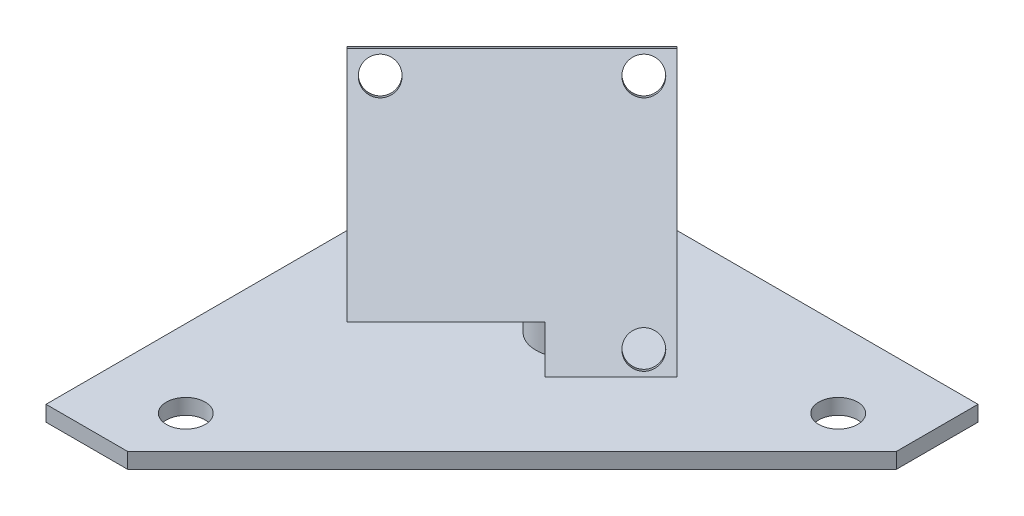
SolidWorks part; units mm, degrees
ref_plane "Front" through (0, 0, 0) normal (0, 0, 1) x (1, 0, 0)
ref_plane "Top" through (0, 0, 0) normal (0, 1, 0) x (1, 0, 0)
ref_plane "Right" through (0, 0, 0) normal (1, 0, 0) x (0, 0, -1)
sketch "草图1" plane through (0, 0, 0) normal (0, 1, 0) x (1, 0, 0)
  line L0 (87.1745, 16.672) -> (1.4976, -69.0049)
  line L1 (0, 0) -> (60, 0)
  line L2 (0, 0) -> (0, -60)
  line L3 (0, -60) -> (60, -60)
  line L4 (60, 0) -> (60, -60)
  line L5 (0, 0) -> (20, 0)
  line L6 (0, 0) -> (0, -20)
  line L7 (0, -20) -> (20, -20)
  line L8 (20, 0) -> (20, -20)
  circle A0 centre (10, -52) radius 2.5
  circle A1 centre (52, -10) radius 2.5
  dimension "D5" = 5
  dimension "D8" = 5
  dimension "D1" = 60
  dimension "D2" = 60
  dimension "D3" = 20
  dimension "D4" = 20
  dimension "D6" = 10
  dimension "D7" = 8
  dimension "D9" = 10
  dimension "D10" = 8
  dimension "D11" = 35
extrude "凸台-拉伸1" add sketch "草图1" along normal blind 2 contours L1 L8 L7 L2 L3 L4
ref_plane "基准面1" through (23.1124, 18.8712, 23.1124) normal (0.6124, 0.5, 0.6124) x (-0.7071, 0, 0.7071)
sketch "草图2" plane through (23.1124, 18.8712, 23.1124) normal (0.6124, 0.5, 0.6124) x (-0.7071, 0, 0.7071)
  line L0 (20.7547, -10.714) -> (-21.3736, -10.714) construction
  line L1 (-15, 16.786) -> (15, 16.786)
  line L2 (-15, 16.786) -> (-15, -13.214)
  line L3 (-15, -13.214) -> (15, -13.214)
  line L4 (15, 16.786) -> (15, -13.214)
  line L5 (-15, 16.786) -> (15, -13.214) construction
  line L6 (-15, -13.214) -> (15, 16.786) construction
  line L7 (0, -2.8326) -> (0, 36.0846) construction
  line L8 (27.4605, 1.786) -> (-33.4746, 1.786) construction
  line L10 (15, 16.786) -> (-3, 16.786)
  line L11 (15, 16.786) -> (15, 11.786)
  line L12 (15, 11.786) -> (-3, 11.786)
  line L13 (-3, 16.786) -> (-3, 11.786)
  circle A0 centre (12, -10.714) radius 2
  circle A1 centre (-12, -10.714) radius 2
  circle A2 centre (-12, 14.286) radius 2
  circle A3 centre (12, 14.286) radius 2
  point P0 (0, 1.786)
  point P23 (0, 1.786)
  dimension "D4" = 4
  dimension "D1" = 30
  dimension "D2" = 30
  dimension "D3" = 12.5
  dimension "D5" = 12
  dimension "D6" = 5
  dimension "D7" = 18
extrude "凸台-拉伸3" add sketch "草图2" along normal blind 2 separate body contours L13 L1 L2 L3 L4 L12 A2 A0 A1
sketch "草图4" plane through (0, 2, 0) normal (0, 1, 0) x (1, 0, 0)
  line L12 (29.4007, -39.3002) -> (31.1685, -41.0679)
  line L13 (16.6728, -52.0281) -> (29.4007, -39.3002)
  line L14 (-6.3082, -29.0471) -> (16.6728, -52.0281)
  line L15 (29.0471, 6.3082) -> (-6.3082, -29.0471)
  line L16 (53.7959, -18.4405) -> (29.0471, 6.3082)
  line L17 (31.1685, -41.0679) -> (53.7959, -18.4405)
  line L18 (29.4007, -39.3002) -> (31.1685, -41.0679)
  line L19 (16.6728, -52.0281) -> (29.4007, -39.3002)
  line L20 (-6.3082, -29.0471) -> (16.6728, -52.0281)
  line L21 (29.0471, 6.3082) -> (-6.3082, -29.0471)
  line L22 (53.7959, -18.4405) -> (29.0471, 6.3082)
  line L23 (31.1685, -41.0679) -> (53.7959, -18.4405)
  circle A0 centre (25.5116, -18.4405) radius 4
  point P3 (25.6845, -22.7848)
  point P4 (26.3426, -19.94)
  point P5 (0, 0)
  point P6 (27.2778, -22.0435)
  point P12 (0, 0)
  point P13 (0, 0)
  point P14 (0, 0)
  dimension "D2" = 8
  dimension "D3" = 15
  dimension "D4" = 20
  dimension "D1" = 10
extrude "凸台-拉伸4" add sketch "草图4" along normal up to surface (14.7556 mm away) contours A0
